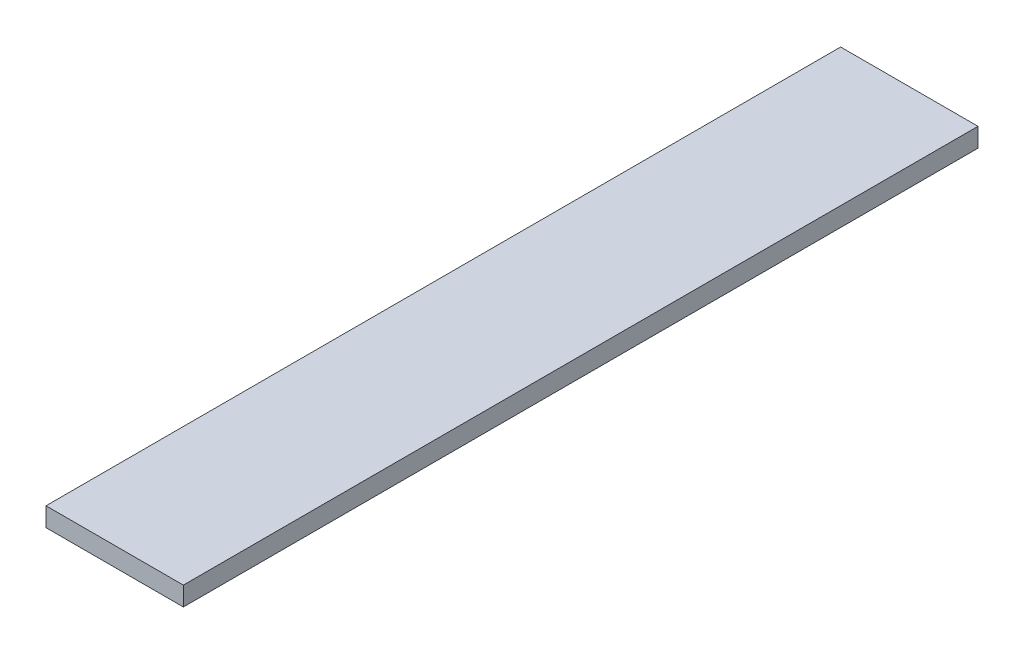
SolidWorks part; units mm, degrees
ref_plane "Front Plane" through (0, 0, 0) normal (0, 0, 1) x (1, 0, 0)
ref_plane "Top Plane" through (0, 0, 0) normal (0, 1, 0) x (1, 0, 0)
ref_plane "Right Plane" through (0, 0, 0) normal (1, 0, 0) x (0, 0, -1)
sketch "Sketch1" plane through (0, 0, 0) normal (0, 1, 0) x (1, 0, 0)
  line L1 (36.18, 209.31) -> (-36.18, 209.31)
  line L2 (36.18, 209.31) -> (36.18, -209.31)
  line L3 (36.18, -209.31) -> (-36.18, -209.31)
  line L4 (-36.18, 209.31) -> (-36.18, -209.31)
  line L5 (36.18, 209.31) -> (-36.18, -209.31) construction
  line L6 (36.18, -209.31) -> (-36.18, 209.31) construction
  point P0 (0, 0)
  dimension "D1" = 72.36
  dimension "D2" = 418.62
extrude "Boss-Extrude1" add sketch "Sketch1" along normal blind 10
